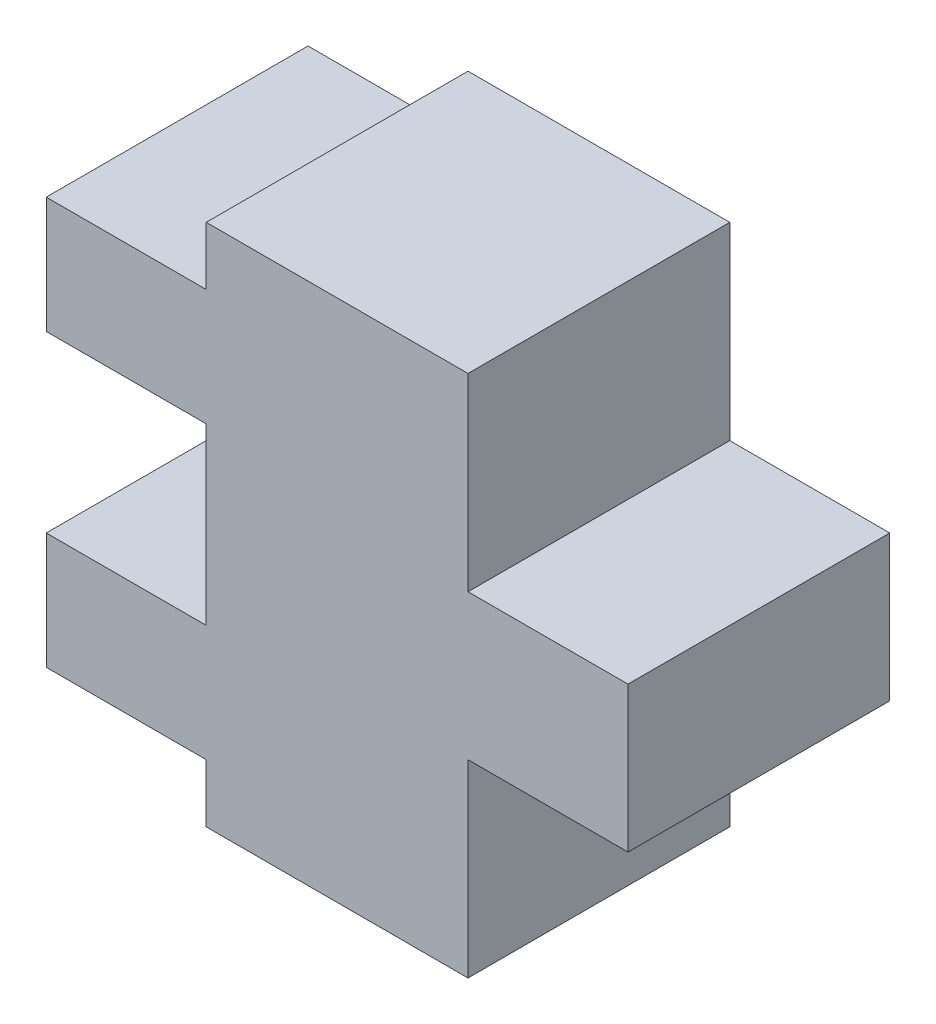
SolidWorks part; units mm, degrees
ref_plane "前视基准面" through (0, 0, 0) normal (0, 0, 1) x (1, 0, 0)
ref_plane "上视基准面" through (0, 0, 0) normal (0, 1, 0) x (1, 0, 0)
ref_plane "右视基准面" through (0, 0, 0) normal (1, 0, 0) x (0, 0, -1)
sketch "草图1" plane through (0, 0, 0) normal (0, 0, 1) x (1, 0, 0)
  line L0 (1, -0.25) -> (0.45, -0.25)
  line L1 (0.45, -0.25) -> (0.45, -0.9)
  line L2 (0.45, -0.9) -> (-0.45, -0.9)
  line L3 (-0.45, -0.9) -> (-0.45, -0.7)
  line L4 (-0.45, -0.7) -> (-1, -0.7)
  line L5 (-1, -0.7) -> (-1, -0.3)
  line L6 (-1, -0.3) -> (-0.45, -0.3)
  line L7 (-0.45, -0.3) -> (-0.45, 0.3)
  line L8 (-0.45, 0.3) -> (-1, 0.3)
  line L9 (-1, 0.3) -> (-1, 0.7)
  line L10 (-1, 0.7) -> (-0.45, 0.7)
  line L11 (-0.45, 0.7) -> (-0.45, 0.9)
  line L12 (-0.45, 0.9) -> (0.45, 0.9)
  line L13 (0.45, 0.9) -> (0.45, 0.25)
  line L14 (0.45, 0.25) -> (1, 0.25)
  line L15 (1, 0.25) -> (1, -0.25)
extrude "Component_Outline" add sketch "草图1" along normal blind 0.9 separate body
sketch3d "3D草图1"
  line L0 (0, 0, 0) -> (1, 0, 0)
  line L1 (0, 0, 0) -> (0, 1, 0)
  line L2 (0, 0, 0) -> (0, 0, 1)
  point P0 (0, 0, 0)
